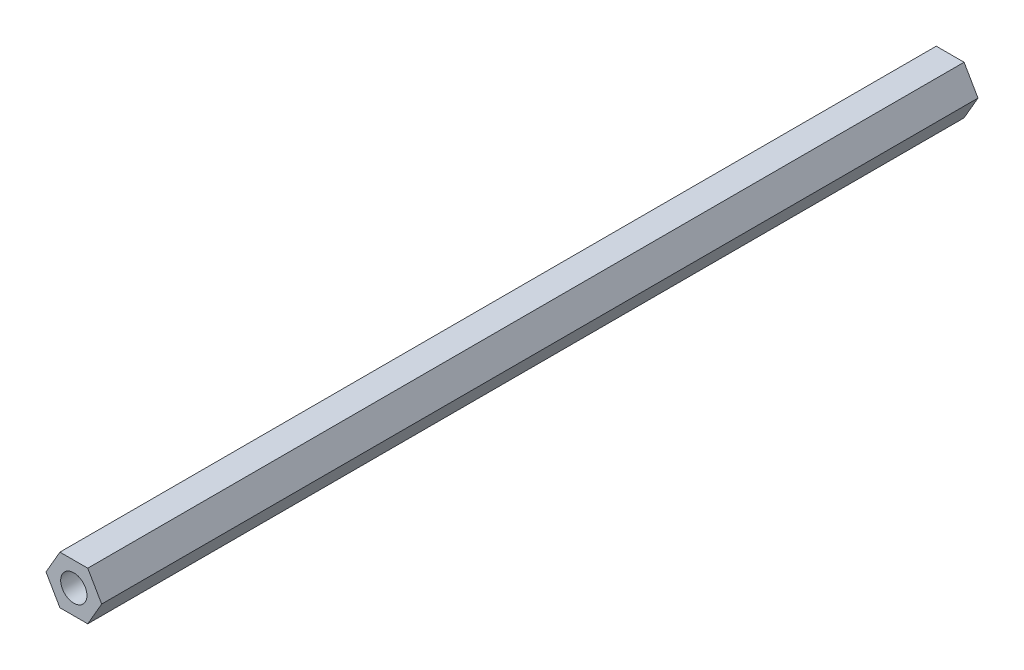
SolidWorks part; units mm, degrees
material "Латунь"
ref_plane "Спереди" through (0, 0, 0) normal (0, 0, 1) x (1, 0, 0)
ref_plane "Сверху" through (0, 0, 0) normal (0, 1, 0) x (1, 0, 0)
ref_plane "Справа" through (0, 0, 0) normal (1, 0, 0) x (0, 0, -1)
sketch "Эскиз1" plane through (0, 0, 0) normal (0, 0, 1) x (1, 0, 0)
  line L1 (1.5877, -2.75) -> (3.1754, 0)
  line L2 (3.1754, 0) -> (1.5877, 2.75)
  line L3 (1.5877, 2.75) -> (-1.5877, 2.75)
  line L4 (-1.5877, 2.75) -> (-3.1754, 0)
  line L5 (-3.1754, 0) -> (-1.5877, -2.75)
  line L6 (-1.5877, -2.75) -> (1.5877, -2.75)
  circle A0 centre (0, 0) radius 2.75 construction
  dimension "D1" = 5.5
extrude "Бобышка-Вытянуть1" add sketch "Эскиз1" along normal blind 100
sketch "Эскиз2" plane through (0, 0, 0) normal (0, 0, -1) x (-1, 0, 0)
  circle A0 centre (0, 0) radius 1.5
  dimension "D1" = 3
extrude "Вырез-Вытянуть1" cut sketch "Эскиз2" against normal blind 10
sketch "Эскиз3" plane through (0, 0, 100) normal (0, 0, 1) x (1, 0, 0)
  circle A0 centre (0, 0) radius 1.5
  dimension "D1" = 3
extrude "Вырез-Вытянуть2" cut sketch "Эскиз3" against normal blind 10
